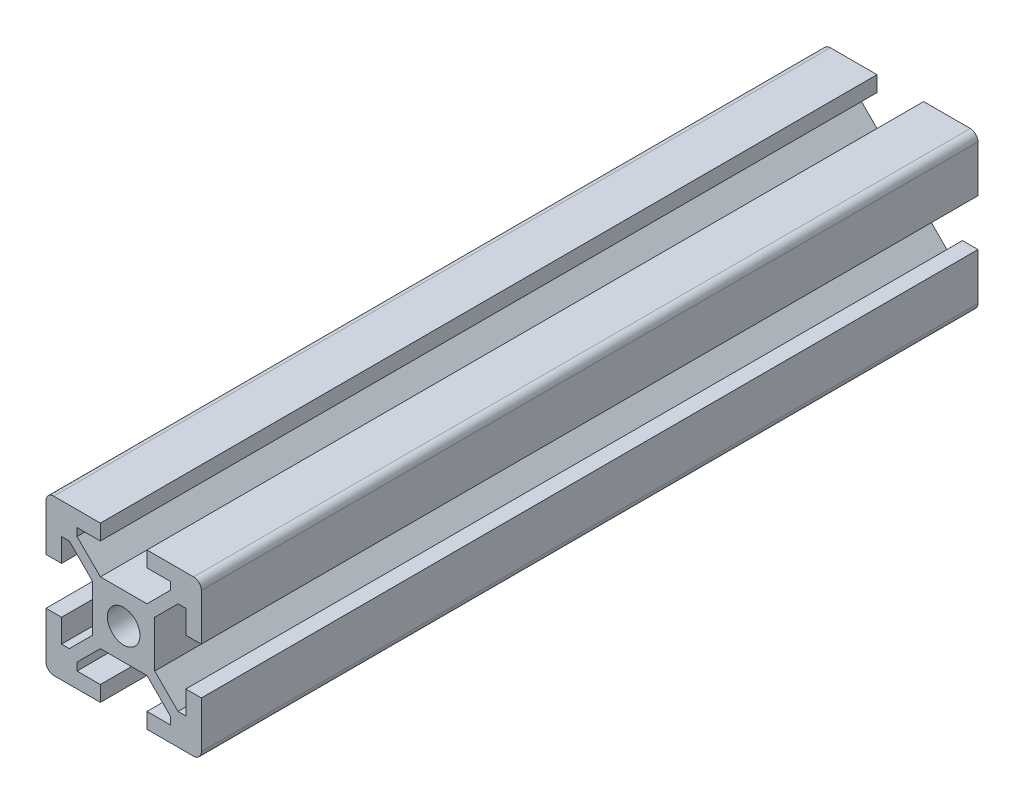
SolidWorks part; units mm, degrees
material "6063-T5"
ref_plane "Front Plane" through (0, 0, 0) normal (0, 0, 1) x (1, 0, 0)
ref_plane "Top Plane" through (0, 0, 0) normal (0, 1, 0) x (1, 0, 0)
ref_plane "Right Plane" through (0, 0, 0) normal (1, 0, 0) x (0, 0, -1)
ref_plane "Plane1" through (0, 0, 0) normal (0, 0, -1) x (-1, 0, 0)
sketch "Sketch1" plane through (0, 0, 0) normal (0, 0, -1) x (-1, 0, 0)
  line L0 (6, -8) -> (3, -8)
  line L1 (3, -8) -> (3, -10)
  line L2 (3, -10) -> (9, -10)
  line L3 (10, -9) -> (10, -3)
  line L4 (10, -3) -> (8, -3)
  line L5 (8, -3) -> (8, -6)
  line L6 (8, -6) -> (7, -6)
  line L7 (7, -6) -> (4, -3)
  line L8 (4, -3) -> (4, 3)
  line L9 (4, 3) -> (7, 6)
  line L10 (7, 6) -> (8, 6)
  line L11 (8, 6) -> (8, 3)
  line L12 (8, 3) -> (10, 3)
  line L13 (10, 3) -> (10, 9)
  line L14 (9, 10) -> (3, 10)
  line L15 (3, 10) -> (3, 8)
  line L16 (3, 8) -> (6, 8)
  line L17 (6, 8) -> (6, 7)
  line L18 (6, 7) -> (3, 4)
  line L19 (3, 4) -> (-3, 4)
  line L20 (-3, 4) -> (-6, 7)
  line L21 (-6, 7) -> (-6, 8)
  line L22 (-6, 8) -> (-3, 8)
  line L23 (-3, 8) -> (-3, 10)
  line L24 (-3, 10) -> (-9, 10)
  line L25 (-10, 9) -> (-10, 3)
  line L26 (-10, 3) -> (-8, 3)
  line L27 (-8, 3) -> (-8, 6)
  line L28 (-8, 6) -> (-7, 6)
  line L29 (-7, 6) -> (-4, 3)
  line L30 (-4, 3) -> (-4, -3)
  line L31 (-4, -3) -> (-7, -6)
  line L32 (-7, -6) -> (-8, -6)
  line L33 (-8, -6) -> (-8, -3)
  line L34 (-8, -3) -> (-10, -3)
  line L35 (-10, -3) -> (-10, -9)
  line L36 (-9, -10) -> (-3, -10)
  line L37 (-3, -10) -> (-3, -8)
  line L38 (-3, -8) -> (-6, -8)
  line L39 (-6, -8) -> (-6, -7)
  line L40 (-6, -7) -> (-3, -4)
  line L41 (-3, -4) -> (3, -4)
  line L42 (3, -4) -> (6, -7)
  line L43 (6, -7) -> (6, -8)
  line L44 (0, 4) -> (0, 0) construction
  line L45 (0, 0) -> (-4, 0) construction
  line L46 (0, 0) -> (4, 0) construction
  line L47 (0, 0) -> (0, -4) construction
  circle A0 centre (0, 0) radius 2.1
  arc A1 (9, -10) -> (10, -9) centre (9, -9) ccw
  arc A2 (10, 9) -> (9, 10) centre (9, 9) ccw
  arc A3 (-9, 10) -> (-10, 9) centre (-9, 9) ccw
  arc A4 (-10, -9) -> (-9, -10) centre (-9, -9) ccw
  point P56 (-4.5, -8)
  dimension "D6" = 1
  dimension "D10" = 4.2
  dimension "D1" = 10
  dimension "D2" = 10
  dimension "D3" = 10
  dimension "D4" = 10
  dimension "D5" = 8
  dimension "D7" = 2
  dimension "D8" = 7
  dimension "D9" = 8
  dimension "D11" = 8
  dimension "D12" = 3
  dimension "D13" = 2
  dimension "D14" = 3
  dimension "D15" = 6
extrude "Boss-Extrude1" add sketch "Sketch1" against normal blind 100
